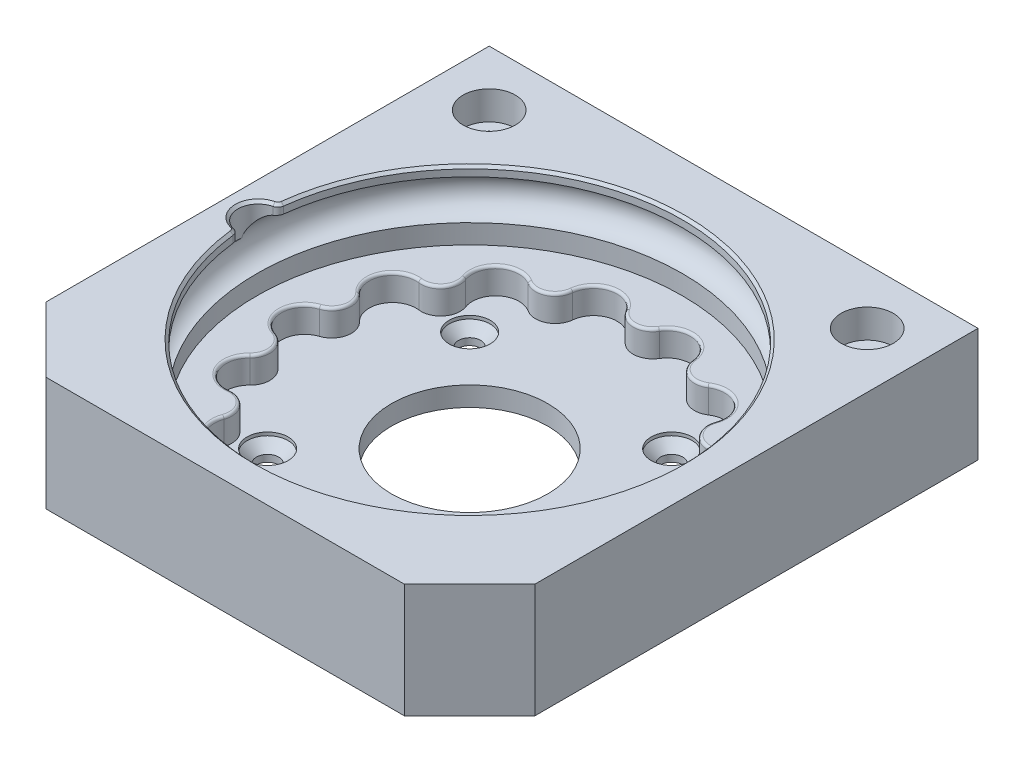
SolidWorks part; units mm, degrees
ref_plane "Front Plane" through (0, 0, 0) normal (0, 0, 1) x (1, 0, 0)
ref_plane "Top Plane" through (0, 0, 0) normal (0, 1, 0) x (1, 0, 0)
ref_plane "Right Plane" through (0, 0, 0) normal (1, 0, 0) x (0, 0, -1)
sketch "Sketch1" plane through (0, 0, 0) normal (0, 1, 0) x (1, 0, 0)
  line L0 (0, 0) -> (7.6226, 33.3969) construction
  line L1 (-37.5, -37.5) -> (37.5, -37.5)
  line L2 (-37.5, -37.5) -> (-37.5, 37.5)
  line L3 (-37.5, 37.5) -> (37.5, 37.5)
  line L4 (37.5, -37.5) -> (37.5, 37.5)
  line L5 (-37.5, -37.5) -> (37.5, 37.5) construction
  line L6 (-37.5, 37.5) -> (37.5, -37.5) construction
  circle A0 centre (0, 0) radius 28.1 construction
  circle A1 centre (0, 28.1) radius 3
  circle A2 centre (12.1921, 25.3172) radius 3
  circle A3 centre (21.9695, 17.5201) radius 3
  circle A4 centre (27.3955, 6.2528) radius 3
  circle A5 centre (27.3955, -6.2528) radius 3
  circle A6 centre (21.9695, -17.5201) radius 3
  circle A7 centre (12.1921, -25.3172) radius 3
  circle A8 centre (0, -28.1) radius 3
  circle A9 centre (-12.1921, -25.3172) radius 3
  circle A10 centre (-21.9695, -17.5201) radius 3
  circle A11 centre (-27.3955, -6.2528) radius 3
  circle A12 centre (-27.3955, 6.2528) radius 3
  circle A13 centre (-21.9695, 17.5201) radius 3
  circle A15 centre (-12.1921, 25.3172) radius 3
  arc A16 (2.5611, 26.5377) -> (9.2068, 25.0208) centre (5.6298, 24.6657) cw
  arc A17 (13.8217, 22.7984) -> (19.1512, 18.5483) centre (15.7743, 19.7803) cw
  arc A18 (22.3448, 14.5436) -> (25.3024, 8.4021) centre (22.7945, 10.9773) cw
  arc A19 (26.4422, 3.4083) -> (26.4422, -3.4083) centre (25.3, 0) cw
  arc A20 (25.3024, -8.4021) -> (22.3448, -14.5436) centre (22.7945, -10.9773) cw
  arc A21 (19.1512, -18.5483) -> (13.8217, -22.7984) centre (15.7743, -19.7803) cw
  arc A22 (9.2068, -25.0208) -> (2.5611, -26.5377) centre (5.6298, -24.6657) cw
  arc A23 (-2.5611, -26.5377) -> (-9.2068, -25.0208) centre (-5.6298, -24.6657) cw
  arc A24 (-13.8217, -22.7984) -> (-19.1512, -18.5483) centre (-15.7743, -19.7803) cw
  arc A25 (-22.3448, -14.5436) -> (-25.3024, -8.4021) centre (-22.7945, -10.9773) cw
  arc A26 (-26.4422, -3.4083) -> (-26.4422, 3.4083) centre (-25.3, 0) cw
  arc A27 (-25.3024, 8.4021) -> (-22.3448, 14.5436) centre (-22.7945, 10.9773) cw
  arc A28 (-19.1512, 18.5483) -> (-13.8217, 22.7984) centre (-15.7743, 19.7803) cw
  arc A29 (-9.2068, 25.0208) -> (-2.5611, 26.5377) centre (-5.6298, 24.6657) cw
  circle A30 centre (0, 0) radius 4.1
  circle A31 centre (0, 0) radius 25.3 construction
  point P0 (0, 0)
  point P46 (6.4297, 28.1702)
  dimension "D1" = 56.2
  dimension "D2" = 6
  dimension "D8" = 8.2
  dimension "D4" = 75
  dimension "D5" = 75
  dimension "D6" = 2.8
  dimension "D3" = 14
  dimension "D7" = 14
sketch "Sketch3" plane through (0, 0, 0) normal (0, 1, 0) x (1, 0, 0)
  line L1 (-37.5, -37.5) -> (37.5, -37.5)
  line L2 (-37.5, -37.5) -> (-37.5, 37.5)
  line L3 (-37.5, 37.5) -> (37.5, 37.5)
  line L4 (37.5, -37.5) -> (37.5, 37.5)
  line L5 (-37.5, -37.5) -> (37.5, 37.5) construction
  line L6 (-37.5, 37.5) -> (37.5, -37.5) construction
  circle A0 centre (0, 0) radius 4.1 construction
  circle A1 centre (0, 0) radius 4.1
  point P0 (0, 0)
extrude "Boss-Extrude1" add sketch "Sketch3" along normal blind 3
sketch "Sketch4" plane through (0, 3, 0) normal (0, 1, 0) x (1, 0, 0)
  line L4 (37.5, -37.5) -> (37.5, 37.5)
  line L5 (37.5, 37.5) -> (-37.5, 37.5)
  line L6 (-37.5, 37.5) -> (-37.5, -37.5)
  line L7 (-37.5, -37.5) -> (37.5, -37.5)
  line L8 (37.5, -37.5) -> (37.5, 37.5)
  line L9 (37.5, 37.5) -> (-37.5, 37.5)
  line L10 (-37.5, 37.5) -> (-37.5, -37.5)
  line L11 (-37.5, -37.5) -> (37.5, -37.5)
  line L12 (-37.5, -37.5) -> (37.5, -37.5)
  line L13 (37.5, -37.5) -> (37.5, 37.5)
  line L14 (37.5, 37.5) -> (-37.5, 37.5)
  line L15 (-37.5, 37.5) -> (-37.5, -37.5)
  line L16 (-37.5, -37.5) -> (37.5, -37.5)
  line L17 (37.5, -37.5) -> (37.5, 37.5)
  line L18 (37.5, 37.5) -> (-37.5, 37.5)
  line L19 (-37.5, 37.5) -> (-37.5, -37.5)
  arc A0 (26.4422, -3.4083) -> (26.4422, 3.4083) centre (25.3, 0) ccw construction
  circle A1 centre (27.3955, -6.2528) radius 3
  circle A2 centre (27.3955, -6.2528) radius 3
  circle A3 centre (12.1921, 25.3172) radius 3
  circle A4 centre (12.1921, 25.3172) radius 3
  circle A5 centre (0, 28.1) radius 3
  circle A6 centre (0, 28.1) radius 3
  circle A7 centre (-27.3955, 6.2528) radius 3
  circle A8 centre (-27.3955, 6.2528) radius 3
  circle A9 centre (-27.3955, -6.2528) radius 3
  circle A10 centre (-27.3955, -6.2528) radius 3
  circle A11 centre (-21.9695, -17.5201) radius 3
  circle A12 centre (-21.9695, -17.5201) radius 3
  circle A13 centre (-12.1921, -25.3172) radius 3
  circle A14 centre (-12.1921, -25.3172) radius 3
  circle A15 centre (0, -28.1) radius 3
  circle A16 centre (0, -28.1) radius 3
  circle A17 centre (12.1921, -25.3172) radius 3
  circle A18 centre (12.1921, -25.3172) radius 3
  circle A19 centre (21.9695, -17.5201) radius 3
  circle A20 centre (21.9695, -17.5201) radius 3
  circle A21 centre (27.3955, 6.2528) radius 3
  circle A22 centre (27.3955, 6.2528) radius 3
  circle A23 centre (21.9695, 17.5201) radius 3
  circle A24 centre (21.9695, 17.5201) radius 3
  circle A25 centre (0, 0) radius 4.1
  circle A26 centre (0, 0) radius 4.1
  circle A27 centre (-12.1921, 25.3172) radius 3
  circle A28 centre (-12.1921, 25.3172) radius 3
  circle A29 centre (-21.9695, 17.5201) radius 3
  circle A30 centre (-21.9695, 17.5201) radius 3
  arc A31 (25.3024, 8.4021) -> (22.3448, 14.5436) centre (22.7945, 10.9773) ccw construction
  arc A32 (19.1512, 18.5483) -> (13.8217, 22.7984) centre (15.7743, 19.7803) ccw construction
  arc A33 (9.2068, 25.0208) -> (2.5611, 26.5377) centre (5.6298, 24.6657) ccw construction
  arc A34 (-19.1512, -18.5483) -> (-13.8217, -22.7984) centre (-15.7743, -19.7803) ccw construction
  arc A35 (-9.2068, -25.0208) -> (-2.5611, -26.5377) centre (-5.6298, -24.6657) ccw construction
  arc A36 (2.5611, -26.5377) -> (9.2068, -25.0208) centre (5.6298, -24.6657) ccw construction
  arc A37 (13.8217, -22.7984) -> (19.1512, -18.5483) centre (15.7743, -19.7803) ccw construction
  arc A38 (22.3448, -14.5436) -> (25.3024, -8.4021) centre (22.7945, -10.9773) ccw construction
  arc A39 (-2.5611, 26.5377) -> (-9.2068, 25.0208) centre (-5.6298, 24.6657) ccw construction
  arc A40 (-13.8217, 22.7984) -> (-19.1512, 18.5483) centre (-15.7743, 19.7803) ccw construction
  arc A41 (-22.3448, 14.5436) -> (-25.3024, 8.4021) centre (-22.7945, 10.9773) ccw construction
  arc A42 (-26.4422, 3.4083) -> (-26.4422, -3.4083) centre (-25.3, 0) ccw construction
  arc A43 (-25.3024, -8.4021) -> (-22.3448, -14.5436) centre (-22.7945, -10.9773) ccw construction
  arc A44 (26.4422, -3.4083) -> (26.4422, 3.4083) centre (25.3, 0) ccw
  arc A45 (25.3024, 8.4021) -> (22.3448, 14.5436) centre (22.7945, 10.9773) ccw
  arc A46 (19.1512, 18.5483) -> (13.8217, 22.7984) centre (15.7743, 19.7803) ccw
  arc A47 (9.2068, 25.0208) -> (2.5611, 26.5377) centre (5.6298, 24.6657) ccw
  arc A48 (-19.1512, -18.5483) -> (-13.8217, -22.7984) centre (-15.7743, -19.7803) ccw
  arc A49 (-9.2068, -25.0208) -> (-2.5611, -26.5377) centre (-5.6298, -24.6657) ccw
  arc A50 (2.5611, -26.5377) -> (9.2068, -25.0208) centre (5.6298, -24.6657) ccw
  arc A51 (13.8217, -22.7984) -> (19.1512, -18.5483) centre (15.7743, -19.7803) ccw
  arc A52 (22.3448, -14.5436) -> (25.3024, -8.4021) centre (22.7945, -10.9773) ccw
  arc A53 (-2.5611, 26.5377) -> (-9.2068, 25.0208) centre (-5.6298, 24.6657) ccw
  arc A54 (-13.8217, 22.7984) -> (-19.1512, 18.5483) centre (-15.7743, 19.7803) ccw
  arc A55 (-22.3448, 14.5436) -> (-25.3024, 8.4021) centre (-22.7945, 10.9773) ccw
  arc A56 (-26.4422, 3.4083) -> (-26.4422, -3.4083) centre (-25.3, 0) ccw
  arc A57 (-25.3024, -8.4021) -> (-22.3448, -14.5436) centre (-22.7945, -10.9773) ccw
  line M24 (37.5, -37.5) -> (37.5, 37.5)
  line M25 (37.5, 37.5) -> (-37.5, 37.5)
  line M26 (-37.5, 37.5) -> (-37.5, -37.5)
  line M27 (-37.5, -37.5) -> (37.5, -37.5)
  dimension "D1" = 0
  dimension "D2" = 0
  dimension "D3" = 0
  dimension "D4" = 0
  dimension "D5" = 0
  dimension "D6" = 0
  dimension "D7" = 0
  dimension "D8" = 0
  dimension "D9" = 0
  dimension "D10" = 0
  dimension "D11" = 0
  dimension "D12" = 0
  dimension "D13" = 0
  dimension "D14" = 0
  dimension "D15" = 0
  dimension "D16" = 0
  dimension "D17" = 0
extrude "Boss-Extrude2" add sketch "Sketch4" along normal blind 4 contours A57 A10 A56 A8 A55 A30 A54 A28 A53 A6 A47 A4 A46 A24 A45 A22 A44 A2 A52 A20 A51 A18 A50 A16 A49 A14 A48 A12 M27 M24 M25 M26 | A24 | A22 | A2 | A20 | A18 | A16 | A14 | A12 | A10 | A8 | A30 | A28 | A6 | A4
sketch "Sketch5" plane through (0, 7, 0) normal (0, 1, 0) x (1, 0, 0)
  line L4 (-37.5, -37.5) -> (37.5, -37.5)
  line L5 (37.5, -37.5) -> (37.5, 37.5)
  line L6 (37.5, 37.5) -> (-37.5, 37.5)
  line L7 (-37.5, 37.5) -> (-37.5, -37.5)
  line L8 (-37.5, -37.5) -> (37.5, -37.5)
  line L9 (37.5, -37.5) -> (37.5, 37.5)
  line L10 (37.5, 37.5) -> (-37.5, 37.5)
  line L11 (-37.5, 37.5) -> (-37.5, -37.5)
  circle A0 centre (0, 0) radius 32.65
  circle A1 centre (-32.65, 0) radius 3.05 construction
  circle A2 centre (0, 0) radius 29.6 construction
  dimension "D2" = 65.3
  dimension "D3" = 6.1
  dimension "D4" = 1.8
  dimension "D1" = 0
extrude "Boss-Extrude3" add sketch "Sketch5" along normal blind 10.5
sketch "Sketch7" plane through (0, 3, 0) normal (0, 1, 0) x (1, 0, 0)
  line L1 (-12.0018, -12.0018) -> (12.0018, -12.0018) construction
  line L2 (-12.0018, -12.0018) -> (-12.0018, 12.0018) construction
  line L3 (-12.0018, 12.0018) -> (12.0018, 12.0018) construction
  line L4 (12.0018, -12.0018) -> (12.0018, 12.0018) construction
  line L5 (-12.0018, -12.0018) -> (12.0018, 12.0018) construction
  line L6 (-12.0018, 12.0018) -> (12.0018, -12.0018) construction
  point P0 (0, 0)
sketch "Sketch8" plane through (0, 17.5, 0) normal (0, 1, 0) x (1, 0, 0)
  line L0 (37.5, 15.533) -> (15.533, 37.5)
  line L1 (-15.533, 37.5) -> (-37.5, 15.533)
  line L2 (-37.5, 15.533) -> (-37.5, -15.533)
  line L3 (-37.5, -15.533) -> (-15.533, -37.5)
  line L4 (-15.533, -37.5) -> (15.533, -37.5)
  line L5 (15.533, -37.5) -> (37.5, -15.533)
  line L6 (37.5, -15.533) -> (37.5, 15.533)
  line L7 (15.533, 37.5) -> (-15.533, 37.5)
  line L8 (-37.5, 37.5) -> (-37.5, -37.5) construction
  circle A0 centre (0, 0) radius 37.5 construction
extrude "Cut-Extrude1" [suppressed] cut sketch "Sketch8" against normal through all flip side to cut
chamfer "Chamfer1" distance 10 angle 45 2 edges at (37.5, 8.75, 37.5) (-37.5, 8.75, 37.5)
sketch "Sketch11" plane through (0, 0, 0) normal (0, 0, 1) x (1, 0, 0)
  line L1 (32.65, 17.5) -> (-32.65, 17.5) construction
  line L4 (0, 0) -> (0, 37.5091) construction
  circle A0 centre (-32.45, 13) radius 3.05
  dimension "D1" = 6.1
  dimension "D2" = 4.5
  dimension "D3" = 64.9
revolve "Cut-Revolve1" cut sketch "Sketch11" angle 360 about L4
sketch "Sketch12" plane through (0, 17.5, 0) normal (0, 1, 0) x (1, 0, 0)
  line L0 (-32.45, 0) -> (0, 0) construction
  line L1 (-35.5, 0) -> (-29.4, 0) construction
  circle A0 centre (-32.45, 0) radius 3.1
  dimension "D1" = 6.2
extrude "Cut-Extrude2" cut sketch "Sketch12" against normal up to vertex (39.8753 mm away)
fillet "Fillet2" radius 1 2 edges at (-32.5025, 16.7717, 3.0996) (-32.5025, 16.7717, -3.0996)
sketch "Sketch14" plane through (0, 0, 0) normal (0, -1, 0) x (1, 0, 0)
  line L1 (-15.5, -15.5) -> (15.5, -15.5) construction
  line L2 (-15.5, -15.5) -> (-15.5, 15.5) construction
  line L3 (-15.5, 15.5) -> (15.5, 15.5) construction
  line L4 (15.5, -15.5) -> (15.5, 15.5) construction
  line L5 (-15.5, -15.5) -> (15.5, 15.5) construction
  line L6 (-15.5, 15.5) -> (15.5, -15.5) construction
  circle A0 centre (0, 0) radius 12
  circle A1 centre (-15.5, 15.5) radius 3.3155 construction
  circle A2 centre (15.5, 15.5) radius 2.5111 construction
  circle A3 centre (15.5, -15.5) radius 2.6783 construction
  circle A4 centre (-15.5, -15.5) radius 2.6959 construction
  dimension "D2" = 24
  dimension "D1" = 31
extrude "Cut-Extrude3" cut sketch "Sketch14" against normal through all
hole_wizard "CSK for M3 Countersunk Flat Head Screw1" positions "Sketch15" profile "Sketch16" countersink size "M3" standard "ISO" end condition through all
sketch "Sketch15" plane through (0, 3, 0) normal (0, 1, 0) x (1, 0, 0)
  point P0 (-15.5, 15.5)
  point P3 (15.5, 15.5)
  point P6 (15.5, -15.5)
  point P9 (-15.5, -15.5)
sketch "Sketch16" plane through (-15.5, 3, -15.5) normal (1, 0, 0) x (0, 0, 1)
  line L0 (0, 0) -> (0, 3)
  line L1 (0, 3) -> (1.7, 3)
  line L2 (1.7, 3) -> (1.7, 1.95)
  line L3 (1.7, 1.95) -> (3.15, 0.5)
  line L4 (3.15, 0.5) -> (3.15, 0)
  line L6 (3.15, 0) -> (0, 0)
  line L7 (-1.7, 1.95) -> (-3.15, 0.5) construction
  line L11 (0, -6.35) -> (0, 107.95) construction
  dimension "Thru Hole Dia." = 3.4
  dimension "Thru Hole Depth" = 3
  dimension "C'Sink Dia." = 6.3
  dimension "C'Sink Angle" = 90
  dimension "Head Clearance" = 0.5
chamfer "Chamfer2" distance 0.4 angle 45 4 edges at (-35.55, 17.5, 0) (-32.6655, 17.5, 3.3212) (-32.6655, 17.5, -3.3212) (32.65, 17.5, 0)
fillet "Fillet3" radius 0.4 28 edges at (-26.0332, 7, 12.5369) (-19.624, 7, 15.6496) (-18.0155, 7, 22.5907) (-10.8905, 7, 22.6143) (-6.4297, 7, 28.1702) (0, 7, 25.1) (6.4297, 7, 28.1702) (10.8905, 7, 22.6143) (18.0155, 7, 22.5907) (19.624, 7, 15.6496) (26.0332, 7, 12.5369) (24.4707, 7, 5.5853) (28.8946, 7, 0) (24.4707, 7, -5.5853) (26.0332, 7, -12.5369) (19.624, 7, -15.6496) (18.0155, 7, -22.5907) (10.8905, 7, -22.6143) (6.4297, 7, -28.1702) (0, 7, -25.1) (-6.4297, 7, -28.1702) (-10.8905, 7, -22.6143) (-18.0155, 7, -22.5907) (-19.624, 7, -15.6496) (-26.0332, 7, -12.5369) (-24.4707, 7, -5.5853) (-28.8946, 7, 0) (-24.4707, 7, 5.5853)
sketch "Sketch17" plane through (0, 0, -37.5) normal (0, 0, -1) x (-1, 0, 0)
  line L4 (-37.5, 0) -> (37.5, 0)
  line L5 (37.5, 0) -> (37.5, 17.5)
  line L6 (37.5, 17.5) -> (-37.5, 17.5)
  line L7 (-37.5, 17.5) -> (-37.5, 0)
  line L8 (-37.5, 0) -> (37.5, 0)
  line L9 (37.5, 0) -> (37.5, 17.5)
  line L10 (37.5, 17.5) -> (-37.5, 17.5)
  line L11 (-37.5, 17.5) -> (-37.5, 0)
  dimension "D1" = 0
extrude "Boss-Extrude4" [suppressed] add sketch "Sketch17" along normal blind 12.5
sketch "Sketch19" [suppressed] plane through (0, 0, -50) normal (0, 0, -1) x (-1, 0, 0)
  line L0 (0, 0) -> (0, 11.3428) construction
  line L1 (-37.5, 0) -> (37.5, 0) construction
  line L2 (37.5, 17.5) -> (-37.5, 17.5) construction
  circle A0 centre (29, 9) radius 2.9
  circle A1 centre (-29, 9) radius 2.9
  dimension "D1" = 8.5
  dimension "D2" = 58
  dimension "D3" = 5.8
extrude "Cut-Extrude4" [suppressed] cut sketch "Sketch19" against normal blind 6.5
hole_wizard "M4 Clearance Hole1" [suppressed] positions "Sketch22" profile "Sketch23" hole size "M4" standard "ISO"
sketch "Sketch22" [suppressed] plane through (0, 0, -50) normal (0, 0, -1) x (-1, 0, 0)
  point P0 (29, 9)
  point P3 (-29, 9)
sketch "Sketch23" plane through (-29, 9, -50) normal (1, 0, 0) x (0, 1, 0)
  line L0 (0, 0) -> (0, 11.3519)
  line L1 (0, 11.3519) -> (2.25, 10)
  line L2 (2.25, 10) -> (2.25, 0)
  line L5 (2.25, 0) -> (0, 0)
  line L10 (0, 11.3519) -> (-2.25, 10) construction
  line L11 (0, -6.35) -> (0, 107.95) construction
  dimension "Hole Dia." = 4.5
  dimension "Hole Depth" = 10
  dimension "Drill Angle" = 118
sketch "Sketch24" plane through (0, 17.5, 0) normal (0, 1, 0) x (1, 0, 0)
  line L0 (37.5, -27.5) -> (37.5, 37.5) construction
  line L1 (-37.5, 37.5) -> (37.5, 37.5)
  line L2 (-37.5, 37.5) -> (-37.5, 40.5)
  line L3 (-37.5, 40.5) -> (37.5, 40.5)
  line L4 (37.5, 37.5) -> (37.5, 40.5)
  point P7 (0, 0)
  dimension "D1" = 3
extrude "Boss-Extrude5" add sketch "Sketch24" against normal up to surface (17.5 mm away) up to face at (-15.5, 0, -13.8)
hole_wizard "CBORE for M4 Hex Socket Head Cap Screw1" positions "Sketch25" profile "Sketch26" counterbore size "M4" standard "ISO" end condition through all
sketch "Sketch25" plane through (0, 17.5, 0) normal (0, 1, 0) x (1, 0, 0)
  line L0 (0, 0) -> (0, 8.9156) construction
  line L3 (37.5, 40.5) -> (-37.5, 40.5) construction
  point P0 (-29, 32)
  point P9 (29, 32)
  dimension "D1" = 58
  dimension "D2" = 8.5
sketch "Sketch26" plane through (-29, 17.5, -32) normal (1, 0, 0) x (0, 0, 1)
  line L0 (0, 0) -> (0, 17.5)
  line L1 (0, 17.5) -> (2.25, 17.5)
  line L3 (2.25, 17.5) -> (2.25, 4.4)
  line L4 (2.25, 4.4) -> (4, 4.4)
  line L5 (4, 4.4) -> (4, 0)
  line L7 (4, 0) -> (0, 0)
  line L11 (0, -6.35) -> (0, 107.95) construction
  dimension "Thru Hole Dia." = 4.5
  dimension "Thru Hole Depth" = 17.5
  dimension "C'Bore Dia." = 8
  dimension "C'Bore Depth" = 4.4
equation "\"N\"= 14"
equation "\"Rr\"= 3"
equation "\"R\"= 28.1"
equation "\"E\"= 1.5"
equation "\"D3@Sketch1\"=\"N\""
equation "\"D1@Sketch1\"=\"R\" *2"
equation "\"D2@Sketch1\"=\"Rr\" *2"
